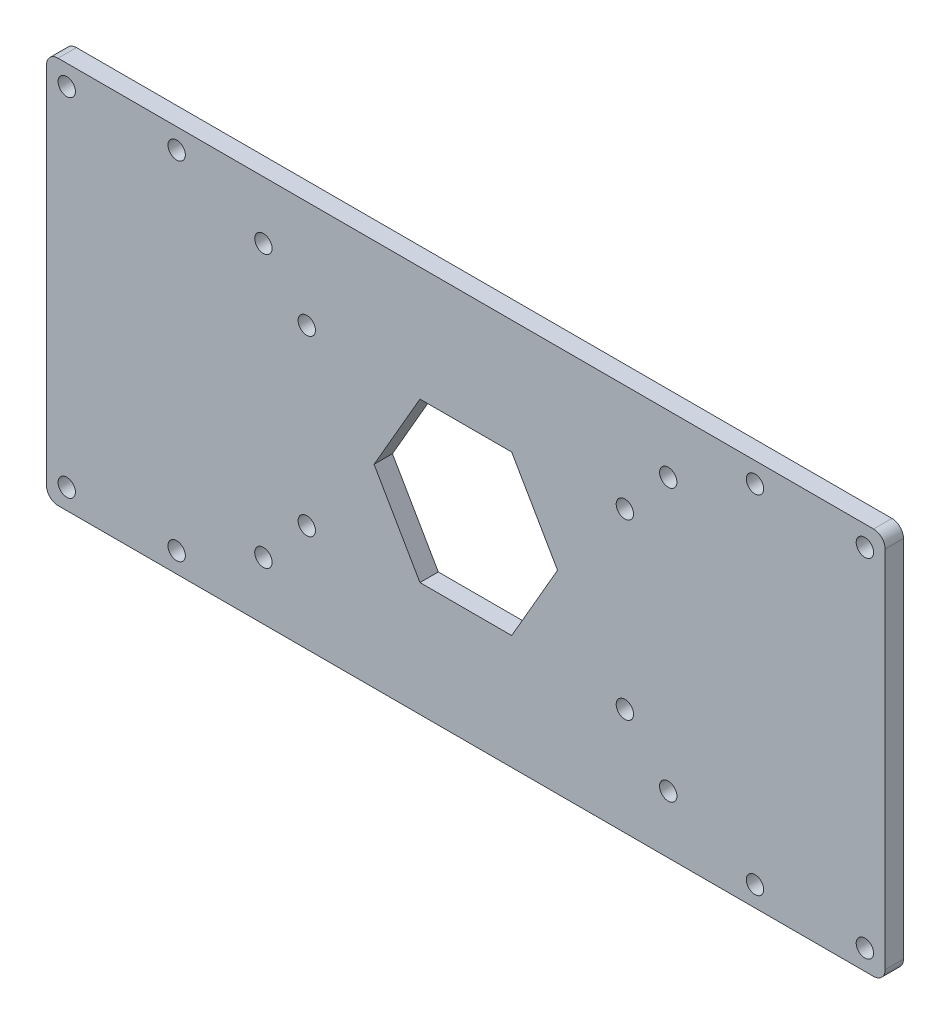
SolidWorks part; units mm, degrees
ref_plane "Front Plane" through (0, 0, 0) normal (0, 0, 1) x (1, 0, 0)
ref_plane "Top Plane" through (0, 0, 0) normal (0, 1, 0) x (1, 0, 0)
ref_plane "Right Plane" through (0, 0, 0) normal (1, 0, 0) x (0, 0, -1)
sketch "Sketch1" plane through (0, 0, 0) normal (0, 0, 1) x (1, 0, 0)
  line L0 (-35, 23.5) -> (35, -23.5) construction
  line L1 (-35, 23.5) -> (35, 23.5) construction
  line L2 (-35, 23.5) -> (-35, -23.5) construction
  line L3 (-35, -23.5) -> (35, -23.5) construction
  line L4 (35, 23.5) -> (35, -23.5) construction
  line L5 (-27.5, 15) -> (27.5, -15) construction
  line L6 (-27.5, 15) -> (27.5, 15) construction
  line L7 (-27.5, 15) -> (-27.5, -15) construction
  line L8 (-27.5, -15) -> (27.5, -15) construction
  line L9 (27.5, 15) -> (27.5, -15) construction
  line L10 (-72.5, -33.5) -> (72.5, 33.5) construction
  line L11 (-72.5, 33.5) -> (72.5, 33.5)
  line L12 (-72.5, 33.5) -> (-72.5, -33.5)
  line L13 (-72.5, -33.5) -> (72.5, -33.5)
  line L14 (72.5, 33.5) -> (72.5, -33.5)
  line L15 (-50, 0) -> (50, 0) construction
  line L16 (-50, -30) -> (-50, 30) construction
  line L17 (50, -30) -> (50, 30) construction
  line L18 (-50, 0) -> (-69, 0) construction
  line L19 (50, 0) -> (69, 0) construction
  line L20 (-69, -30) -> (-69, 30) construction
  line L21 (69, -30) -> (69, 30) construction
  line L22 (-69, 0) -> (-72.5, 0) construction
  line L23 (69, 30) -> (69, 33.5) construction
  line L24 (69, -30) -> (69, -33.5) construction
  line L25 (69, -30) -> (72.5, -30) construction
  line L27 (69, 0) -> (72.5, 0) construction
  line L28 (-69, -30) -> (-72.5, -30) construction
  line L29 (-50, -30) -> (-46.5, -30) construction
  line L30 (-69, -30) -> (-69, -33.5) construction
  line L31 (-69, 30) -> (-69, 53.5) construction
  line L32 (15.8627, 0) -> (7.9314, 13.7375)
  line L33 (7.9314, 13.7375) -> (-7.9314, 13.7375)
  line L34 (-7.9314, 13.7375) -> (-15.8627, 0)
  line L35 (-15.8627, 0) -> (-7.9314, -13.7375)
  line L36 (-7.9314, -13.7375) -> (7.9314, -13.7375)
  line L37 (7.9314, -13.7375) -> (15.8627, 0)
  circle A0 centre (-35, 23.5) radius 1.5
  circle A1 centre (35, 23.5) radius 1.5
  circle A2 centre (35, -23.5) radius 1.5
  circle A3 centre (-35, -23.5) radius 1.5
  circle A4 centre (-27.5, 15) radius 1.5
  circle A5 centre (27.5, 15) radius 1.5
  circle A6 centre (27.5, -15) radius 1.5
  circle A7 centre (-27.5, -15) radius 1.5
  circle A8 centre (-69, 30) radius 1.5
  circle A9 centre (-50, 30) radius 1.5
  circle A10 centre (-50, -30) radius 1.5
  circle A11 centre (-69, -30) radius 1.5
  circle A12 centre (50, -30) radius 1.5
  circle A13 centre (69, -30) radius 1.5
  circle A14 centre (50, 30) radius 1.5
  circle A15 centre (69, 30) radius 1.5
  circle A16 centre (0, 0) radius 13.7375 construction
  point P4 (0, 0)
  point P14 (0, 0)
  point P23 (0, 0)
  point P26 (0, 0)
  point P31 (50, 0)
  point P32 (-50, 0)
  point P39 (-69, 0)
  point P40 (69, 0)
  dimension "D3" = 3
  dimension "D6" = 3
  dimension "D1" = 47
  dimension "D2" = 70
  dimension "D4" = 30
  dimension "D5" = 55
  dimension "D7" = 3.5
  dimension "D8" = 145
  dimension "D9" = 100
  dimension "D10" = 60
  dimension "D11" = 60
  dimension "D12" = 19
  dimension "D13" = 3.5
  dimension "D14" = 3.5
  dimension "D15" = 3.5
  dimension "D16" = 23.5
  dimension "D17" = 3.5
extrude "Boss-Extrude1" add sketch "Sketch1" along normal blind 3.175
fillet "Fillet2" radius 2 4 edges at (-72.5, -33.5, 1.5875) (72.5, -33.5, 1.5875) (72.5, 33.5, 1.5875) (-72.5, 33.5, 1.5875)
